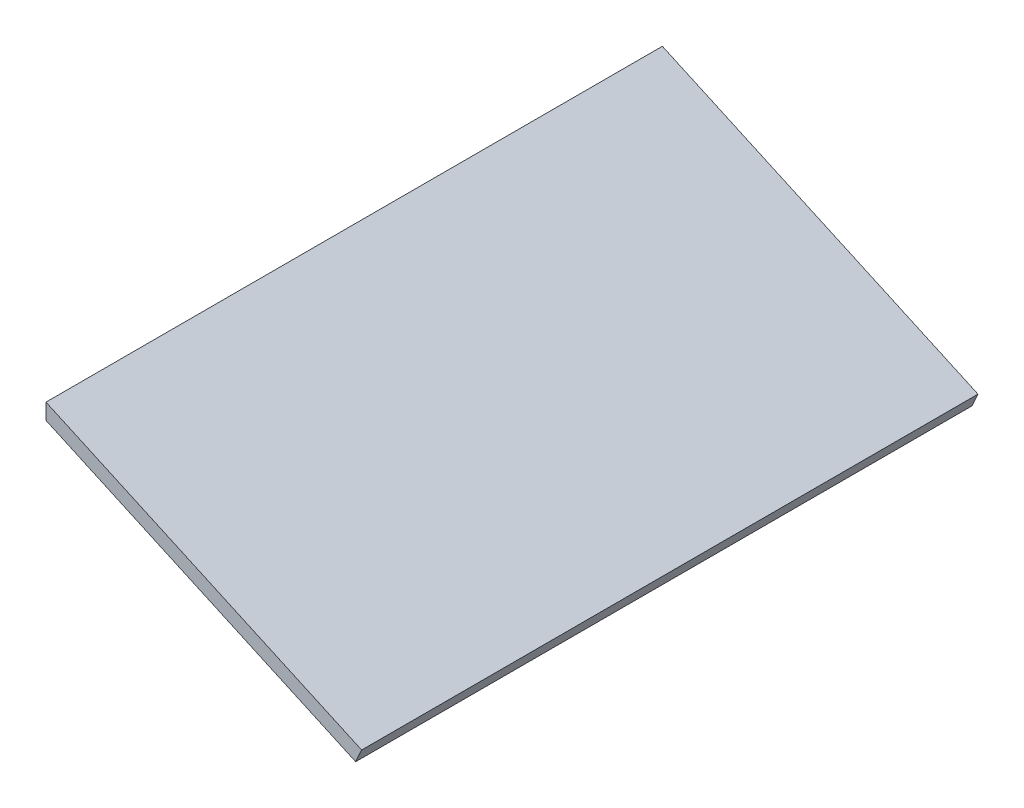
SolidWorks part; units mm, degrees
material "Pine"
ref_plane "Front Plane" through (0, 0, 0) normal (0, 0, 1) x (1, 0, 0)
ref_plane "Top Plane" through (0, 0, 0) normal (0, 1, 0) x (1, 0, 0)
ref_plane "Right Plane" through (0, 0, 0) normal (1, 0, 0) x (0, 0, -1)
sketch "Sketch3" plane through (0, 0, 0) normal (0, 0, 1) x (1, 0, 0)
  line L0 (-108.5345, -3.9032) -> (-108.5345, 1464.0363)
  line L1 (-108.5345, -3.9032) -> (-870.5345, -3.9032)
  line L2 (-870.5345, -3.9032) -> (-870.5345, 625.8363)
  line L3 (-972.1345, 737.9573) -> (-972.1345, 834.2968)
  line L4 (-768.9345, 834.2968) -> (-768.9345, 986.6968)
  line L5 (-972.1345, 834.2968) -> (-768.9345, 834.2968)
  line L6 (-528.0858, 1843.9468) -> (-737.1845, 1843.9468)
  line L7 (-968.4148, 728.977) -> (-874.2542, 634.8165)
  line L8 (-737.1845, 1672.0154) -> (-737.1845, 1762.6932)
  line L9 (-520.195, 1875.6968) -> (-756.2345, 1875.6968)
  line L10 (-112.2542, 1473.0165) -> (-511.2148, 1871.977)
  line L11 (-737.1845, 1692.941) -> (-241.631, 1467.6894)
  line L12 (-596.8655, 1608.234) -> (-737.1845, 983.1768)
  line L13 (-763.9746, 985.3593) -> (-203.7845, 834.2968)
  line L14 (-761.4898, 1669.1128) -> (-638.6318, 1613.2683)
  line L15 (-631.4955, 1598.9249) -> (-768.9345, 986.6968)
  line L16 (-768.9345, 1680.6745) -> (-768.9345, 1862.9968)
  line L17 (-737.1845, 1780.4468) -> (-737.1845, 1843.9468)
  line L18 (-737.1845, 1692.941) -> (-737.1845, 1843.9468) construction
  line L19 (-737.1845, 1692.941) -> (-737.1845, 1762.6932) construction
  line L20 (-838.7845, -3.9032) -> (-838.7845, 834.2968)
  line L21 (-745.0674, 1675.5986) -> (-249.5139, 1450.347) construction
  line L22 (-140.2845, -3.9032) -> (-140.2845, 1456.1455)
  line L23 (-140.2845, 1456.1455) -> (-528.0858, 1843.9468)
  line L24 (-537.8111, 1581.3911) -> (-673.6845, 976.1369)
  line L25 (-768.9345, 966.9663) -> (-203.7845, 814.5663)
  line L26 (-737.1845, 1672.0154) -> (-203.7845, 1429.5608)
  line L27 (-528.0858, 1843.9468) -> (-554.3883, 1780.4468)
  line L28 (-140.2845, 1456.1455) -> (-203.7845, 1429.8429)
  line L29 (-775.2845, -3.9032) -> (-775.2845, 834.2968)
  line L30 (-773.8944, 968.3038) -> (-208.7444, 815.9038) construction
  line L31 (-203.7845, -3.9032) -> (-203.7845, 1429.8429)
  line L32 (-203.7845, 1429.8429) -> (-554.3883, 1780.4468)
  line L33 (-554.3883, 1780.4468) -> (-737.1845, 1780.4468)
  line L34 (-768.9345, 966.9663) -> (-763.9746, 985.3593)
  line L35 (-737.1845, 1762.6932) -> (-369.5099, 1595.5683)
  line L36 (-673.6845, 1733.8295) -> (-599.2171, 1699.9807) construction
  line L37 (-737.1845, 1692.941) -> (-625.4936, 1642.1724) construction
  line L38 (-538.5586, 1578.0615) -> (-673.6845, 976.1369) construction
  line L39 (-600.5166, 1591.9704) -> (-737.1845, 983.1768) construction
  line L40 (-554.3883, 1780.4468) -> (-673.6845, 1780.4468) construction
  line L41 (-203.7845, 91.3468) -> (-203.7845, 1429.8429) construction
  line L42 (-140.2845, 27.8468) -> (-140.2845, 1456.1455) construction
  line L43 (-775.2845, 91.3468) -> (-775.2845, 625.8363) construction
  line L44 (-838.7845, 27.8468) -> (-838.7845, 625.8363) construction
  line L45 (-203.7845, 91.3468) -> (-775.2845, 91.3468) construction
  line L46 (-140.2845, 27.8468) -> (-838.7845, 27.8468) construction
  line L47 (-940.3845, 745.8481) -> (-851.8036, 657.2672) construction
  line L48 (-843.7807, 739.0468) -> (-806.9023, 702.1685) construction
  line L49 (-843.7807, 739.0468) -> (-673.6845, 739.0468) construction
  line L50 (-940.3845, 802.5468) -> (-737.1845, 802.5468) construction
  line L51 (-940.3845, 745.8481) -> (-940.3845, 802.5468) construction
  line L52 (-843.7807, 739.0468) -> (-843.7807, 739.0468) construction
  line L53 (-673.6845, 1733.8295) -> (-673.6845, 1780.4468) construction
  line L54 (-756.2345, 1692.941) -> (-756.2345, 1792.2779) construction
  line L55 (-756.2345, 1792.2779) -> (-361.627, 1612.9108) construction
  line L56 (-673.6845, 739.0468) -> (-673.6845, 976.1369) construction
  line L57 (-737.1845, 802.5468) -> (-737.1845, 983.1768) construction
  line L58 (-768.9345, 986.6968) -> (-203.7845, 834.2968) construction
  line L59 (-203.7845, 834.2968) -> (-208.7444, 815.9038)
  line L60 (-768.9345, 901.198) -> (-203.7845, 748.798)
  line L61 (-846.7775, 922.1894) -> (-163.9675, 738.0608) construction
  line L62 (-768.9345, 966.9663) -> (-208.7444, 815.9038) construction
  line L64 (-808.7515, 1063.2022) -> (-125.9415, 879.0737) construction
  line L65 (-125.9415, 879.0737) -> (-163.9675, 738.0608) construction
  line L66 (-846.7775, 922.1894) -> (-808.7515, 1063.2022) construction
  arc A0 (-108.5345, 1464.0363) -> (-112.2542, 1473.0165) centre (-121.2345, 1464.0363) ccw
  arc A1 (-511.2148, 1871.977) -> (-520.195, 1875.6968) centre (-520.195, 1862.9968) ccw
  arc A2 (-768.9345, 1862.9968) -> (-756.2345, 1875.6968) centre (-756.2345, 1862.9968) cw
  arc A3 (-768.9345, 1680.6745) -> (-761.4898, 1669.1128) centre (-756.2345, 1680.6745) ccw
  arc A4 (-631.4955, 1598.9249) -> (-638.6318, 1613.2683) centre (-643.8871, 1601.7067) ccw
  arc A5 (-972.1345, 737.9573) -> (-968.4148, 728.977) centre (-959.4345, 737.9573) ccw
  arc A6 (-870.5345, 625.8363) -> (-874.2542, 634.8165) centre (-883.2345, 625.8363) ccw
  arc A7 (-737.1845, 1843.9468) -> (-737.1845, 1843.9468) centre (-737.1845, 1843.9468) cw
  arc A8 (-737.1845, 1692.941) -> (-737.1845, 1692.941) centre (-737.1845, 1692.941) ccw
  arc A12 (-140.2845, 1456.1455) -> (-140.2845, 1456.1455) centre (-140.2845, 1456.1455) ccw
  arc A13 (-528.0858, 1843.9468) -> (-528.0858, 1843.9468) centre (-528.0858, 1843.9468) ccw
  arc A14 (-600.5166, 1591.9704) -> (-625.4936, 1642.1724) centre (-643.8871, 1601.7067) ccw construction
  arc A16 (-203.7845, 1429.8429) -> (-203.7845, 1429.8429) centre (-203.7845, 1429.8429) ccw
  arc A17 (-554.3883, 1780.4468) -> (-554.3883, 1780.4468) centre (-554.3883, 1780.4468) ccw
  arc A18 (-673.6845, 1780.4468) -> (-673.6845, 1780.4468) centre (-673.6845, 1780.4468) cw
  arc A19 (-673.6845, 1733.8295) -> (-673.6845, 1733.8295) centre (-673.6845, 1733.8295) ccw
  arc A20 (-838.7845, 625.8363) -> (-851.8036, 657.2672) centre (-883.2345, 625.8363) ccw construction
  arc A21 (-775.2845, 625.8363) -> (-806.9023, 702.1685) centre (-883.2345, 625.8363) ccw construction
  arc A22 (-843.7807, 739.0468) -> (-843.7807, 739.0468) centre (-843.7807, 739.0468) ccw construction
  arc A23 (-940.3845, 745.8481) -> (-940.3845, 745.8481) centre (-940.3845, 745.8481) ccw construction
  arc A24 (-756.2345, 1692.941) -> (-745.0674, 1675.5986) centre (-737.1845, 1692.941) ccw construction
  dimension "D1" = 12.7
  dimension "D2" = 31.75
  dimension "D3" = 63.5
  dimension "D4" = 19.05
  dimension "D5" = 19.05
  dimension "D6" = 63.5
sketch "Sketch6" plane through (0, 0, 0) normal (0, 0, 1) x (1, 0, 0)
  line L0 (-737.1845, 1672.0154) -> (-737.1845, 1692.941)
  line L1 (-737.1845, 1692.941) -> (-320.9649, 1503.7503)
  line L2 (-737.1845, 1672.0154) -> (-328.8479, 1486.4078)
  line L5 (-320.9649, 1503.7503) -> (-328.8479, 1486.4078)
extrude "Boss-Extrude1" add sketch "Sketch6" along normal blind 812.8
